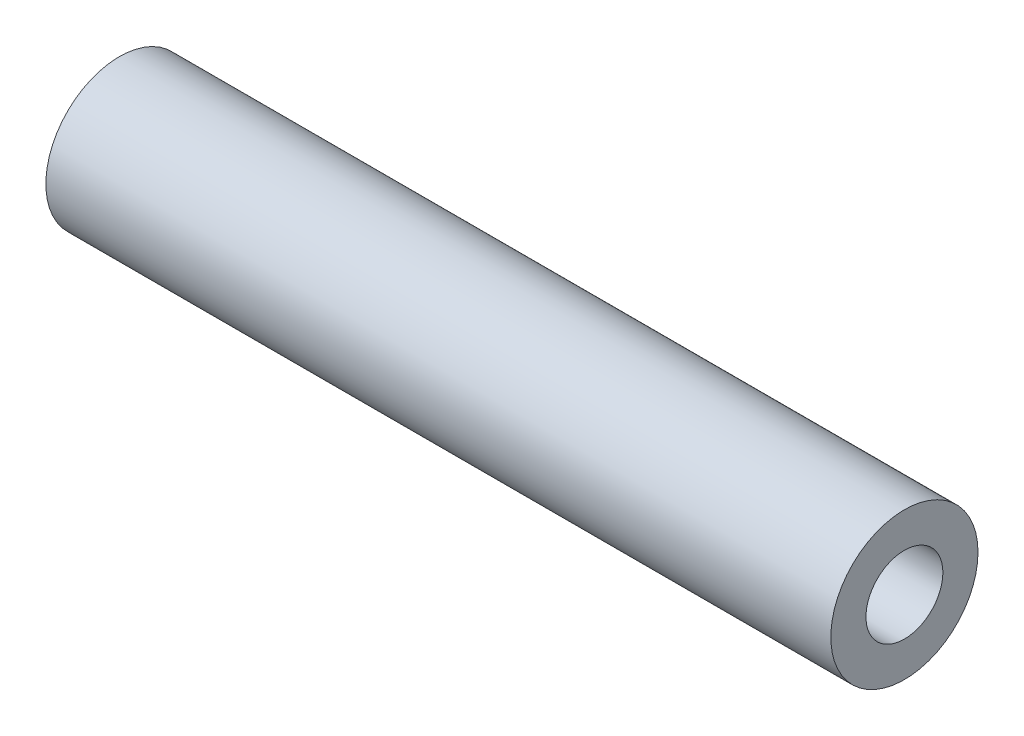
SolidWorks part; units mm, degrees
material "6061-T6 (SS)"
ref_plane "Front Plane" through (0, 0, 0) normal (0, 0, 1) x (1, 0, 0)
ref_plane "Top Plane" through (0, 0, 0) normal (0, 1, 0) x (1, 0, 0)
ref_plane "Right Plane" through (0, 0, 0) normal (1, 0, 0) x (0, 0, -1)
sketch "Sketch1" plane through (0, 0, 0) normal (1, 0, 0) x (0, 0, -1)
  circle A0 centre (0, 0) radius 2.4892
  circle A1 centre (0, 0) radius 4.7625
  dimension "D1" = 4.9784
  dimension "D2" = 9.525
extrude "Boss-Extrude1" add sketch "Sketch1" along normal mid plane 50.8
